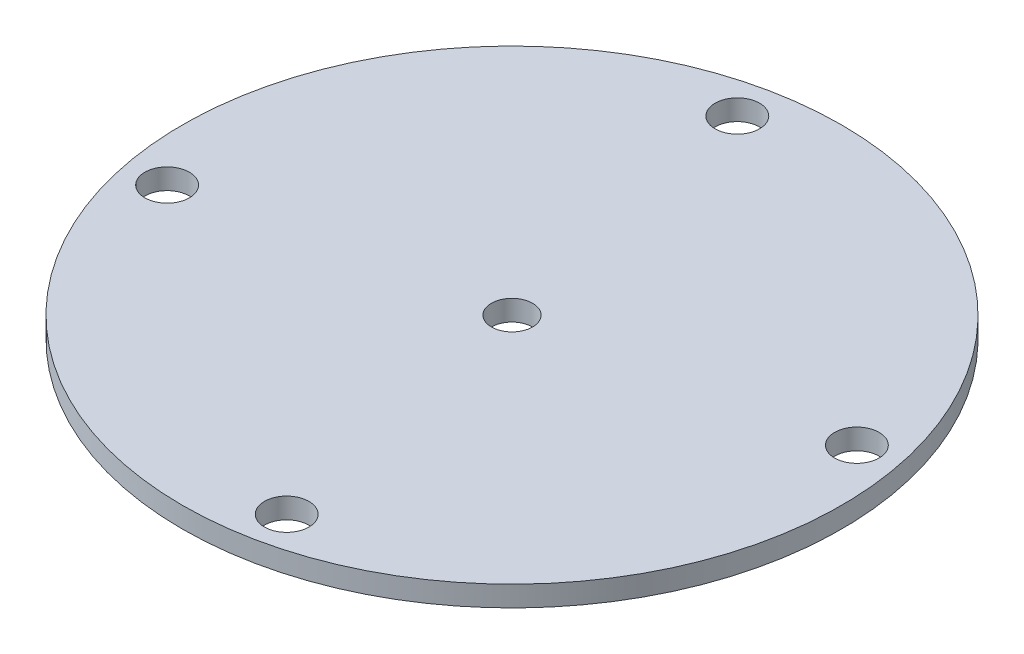
SolidWorks part; units mm, degrees
ref_plane "Front Plane" through (0, 0, 0) normal (0, 0, 1) x (1, 0, 0)
ref_plane "Top Plane" through (0, 0, 0) normal (0, 1, 0) x (1, 0, 0)
ref_plane "Right Plane" through (0, 0, 0) normal (1, 0, 0) x (0, 0, -1)
sketch "Sketch1" plane through (0, 0, 0) normal (0, 1, 0) x (1, 0, 0)
  circle A0 centre (0, 0) radius 50.8
  circle A1 centre (0, 0) radius 3.175
  dimension "D1" = 101.6
  dimension "D2" = 6.35
extrude "Boss-Extrude1" add sketch "Sketch1" along normal blind 3.175 contours A1 | A0
sketch "Sketch2" plane through (0, 3.175, 0) normal (0, 1, 0) x (1, 0, 0)
  circle A0 centre (-9.2146, 43.9456) radius 3.429
  circle A1 centre (0, 0) radius 146.05
  circle A2 centre (0, 0) radius 146.05
  circle A3 centre (0, 0) radius 146.05
  circle A4 centre (0, 0) radius 146.05
  circle A5 centre (43.9456, 9.2146) radius 3.429
  circle A6 centre (9.2146, -43.9456) radius 3.429
  circle A7 centre (-43.9456, -9.2146) radius 3.429
  dimension "D3" = 6.858
  dimension "D4" = 6.858
  dimension "D5" = 6.858
  dimension "D6" = 6.858
  dimension "D1" = 0
  dimension "D2" = 0
extrude "Cut-Extrude1" cut sketch "Sketch2" against normal blind 3.175 contours A0 | A7 | A5 | A6
equation "\"D4@Sketch2\"=\"D3@Sketch2\""
equation "\"D5@Sketch2\"=\"D3@Sketch2\""
equation "\"D6@Sketch2\"=\"D3@Sketch2\""
